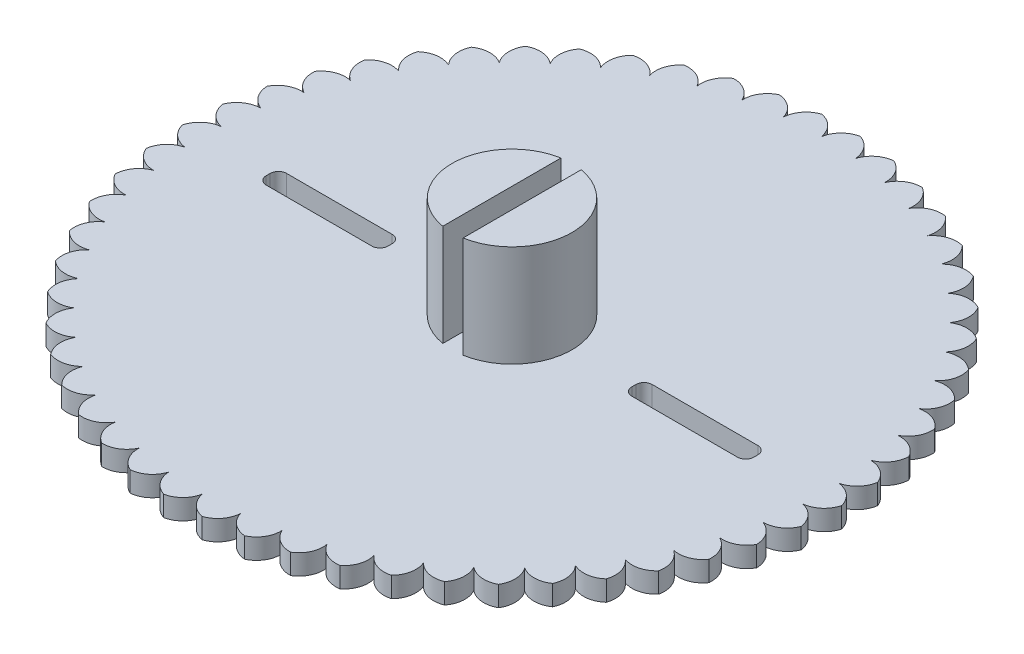
SolidWorks part; units mm, degrees
material "PVC 0.007 Plasticized"
ref_plane "Front Plane" through (0, 0, 0) normal (0, 0, 1) x (1, 0, 0)
ref_plane "Top Plane" through (0, 0, 0) normal (0, 1, 0) x (1, 0, 0)
ref_plane "Right Plane" through (0, 0, 0) normal (1, 0, 0) x (0, 0, -1)
sketch "Sketch1" plane through (0, 0, 0) normal (0, 1, 0) x (1, 0, 0)
  circle A0 centre (0, 0) radius 81.2
  dimension "D1" = 162.4
extrude "Boss-Extrude1" add sketch "Sketch1" along normal blind 5
sketch "Sketch4" plane through (0, 5, 0) normal (0, 1, 0) x (1, 0, 0)
  circle A0 centre (0, 0) radius 14.75
  dimension "D1" = 29.5
extrude "Boss-Extrude2" add sketch "Sketch4" along normal blind 25
sketch "Sketch2" plane through (0, 5, 0) normal (0, 1, 0) x (1, 0, 0)
  line L0 (0, 81.2) -> (0, 76.2)
  circle A0 centre (0, 0) radius 81.2 construction
  arc A1 (0, 76.2) -> (-5, 81.0459) centre (-5.9009, 75.1139) ccw
  arc A2 (0, 76.2) -> (5, 81.0459) centre (5.9009, 75.1139) cw
  dimension "D2" = 6
  dimension "D1" = 5
  dimension "D3" = 5
  dimension "D4" = 10
extrude "Cut-Extrude2" cut sketch "Sketch2" against normal through all contours A1 L0 | L0 A2 A1
pattern_circular "CirPattern2" count 54 over 360 about axis through (0, 0, 0) along (0, 1, 0) of "Cut-Extrude2"
sketch "Sketch6" plane through (0, 5, 0) normal (0, 1, 0) x (1, 0, 0)
  line L0 (-1000, 0) -> (49000, 0) construction
  line L1 (0, -1000) -> (0, 49000) construction
  line L3 (-58, -2.5) -> (-32, -2.5)
  line L4 (-60, -0.5) -> (-60, 0.5)
  line L5 (-58, 2.5) -> (-32, 2.5)
  line L6 (-30, -0.5) -> (-30, 0.5)
  line L7 (-60, -2.5) -> (-30, 2.5) construction
  line L8 (-60, 2.5) -> (-30, -2.5) construction
  arc A0 (-32, -2.5) -> (-30, -0.5) centre (-32, -0.5) ccw
  arc A1 (-32, 2.5) -> (-30, 0.5) centre (-32, 0.5) cw
  arc A2 (-58, -2.5) -> (-60, -0.5) centre (-58, -0.5) cw
  arc A3 (-60, 0.5) -> (-58, 2.5) centre (-58, 0.5) cw
  point P4 (-45, 0)
  dimension "D4" = 2
  dimension "D1" = 30
  dimension "D2" = 5
  dimension "D3" = 45
extrude "Cut-Extrude4" cut sketch "Sketch6" against normal through all
sketch "Sketch5" plane through (0, 30, 0) normal (0, 1, 0) x (1, 0, 0)
  line L1 (2.5, -14.75) -> (-2.5, -14.75)
  line L2 (2.5, -14.75) -> (2.5, 14.75)
  line L3 (2.5, 14.75) -> (-2.5, 14.75)
  line L4 (-2.5, -14.75) -> (-2.5, 14.75)
  line L5 (2.5, -14.75) -> (-2.5, 14.75) construction
  line L6 (2.5, 14.75) -> (-2.5, -14.75) construction
  point P0 (0, 0)
  dimension "D1" = 29.5
  dimension "D2" = 5
extrude "Cut-Extrude3" cut sketch "Sketch5" against normal blind 25
pattern_linear "LPattern1" count 2 spacing 90 along (1, 0, 0) of "Cut-Extrude4"
